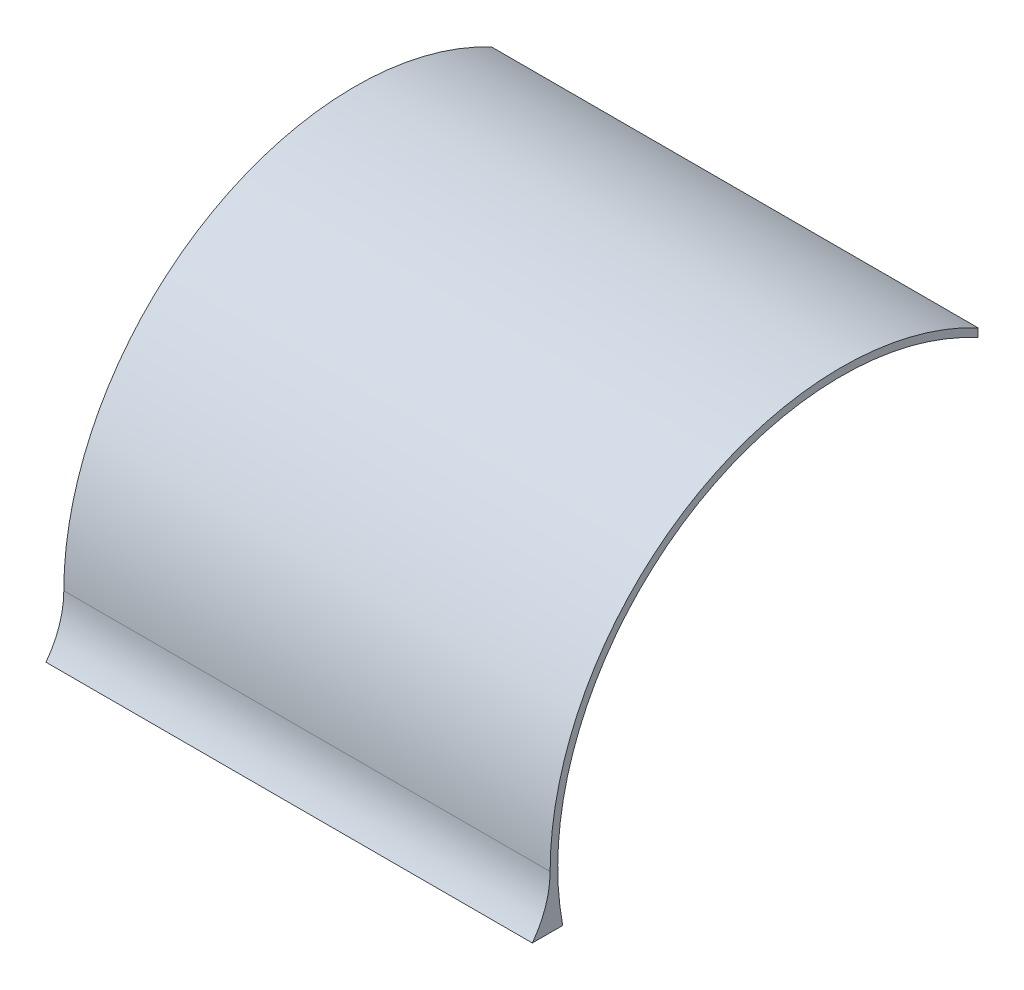
SolidWorks part; units mm, degrees
ref_plane "Alzado" through (0, 0, 0) normal (0, 0, 1) x (1, 0, 0)
ref_plane "Planta" through (0, 0, 0) normal (0, 1, 0) x (1, 0, 0)
ref_plane "Vista lateral" through (0, 0, 0) normal (1, 0, 0) x (0, 0, -1)
sketch "Croquis1" plane through (0, 0, 0) normal (1, 0, 0) x (0, 0, -1)
  line L0 (-94.1687, -17.44) -> (-91.625, -17.44)
  line L1 (45, 84.5393) -> (45, 81.6963)
  circle A0 centre (0, 0) radius 93.27
  circle A1 centre (0, 0) radius 95.77
  dimension "D2" = 93.27
  dimension "D1" = 2.5
  dimension "D3" = 45
  dimension "D4" = 17.44
extrude "Saliente-Extruir1" add sketch "Croquis1" along normal blind 160 contours L1 A1 L0 A0
sketch "Croquis2" plane through (160, 0, 0) normal (1, 0, 0) x (0, 0, -1)
  line L0 (-94.1687, -17.44) -> (-101.625, -17.44)
  line L1 (0, 0) -> (-95.77, 0) construction
  line L2 (-95.77, 0) -> (-95.77, -17.44) construction
  line L3 (-100.177, -17.44) -> (-100.177, -18.7474) construction
  line L4 (-100.177, -18.7474) -> (-97.057, -18.7474) construction
  line L5 (-97.057, -18.7474) -> (-97.057, -17.44) construction
  circle A1 centre (0, 0) radius 95.77 construction
  circle A2 centre (0, 0) radius 93.27 construction
  arc A3 (-95.77, 0) -> (-101.625, -17.44) centre (-124.6714, 0) cw
  arc A4 (-95.77, 0) -> (-94.1687, -17.44) centre (0, 0) ccw
  dimension "D1" = 10
  dimension "D2" = 3.12
extrude "Saliente-Extruir3" add sketch "Croquis2" against normal blind 160
equation "\"D1@Croquis1\"= \"GROSOR_PARED_IMPRESION\""
equation "\"venesta\"= 4'grosor de la venesta"
equation "\"policarbonato\"= 4'grosor del policarbonato"
equation "\"carton_trupan\"= 3'grosor del carton trupan caso laser"
equation "\"ancho_tot\"= 310'ancho tot sin llantas"
equation "\"largo_tot\"= 400'largo tot sin camera"
equation "\"alto_estimado\"= 300'alto estimado sin lidar"
equation "\"altoparaqpaselabotella\"= 75'alto estimado para que encaje la botella"
equation "\"alturaruedaloca\"= 22"
equation "\"anchoruedaloca\"= 35"
equation "\"anchopiso1motorybaterias\"= 150"
equation "\"dist-pisorampa\"= 5"
equation "\"anchoultimopiso\"= 170"
equation "\"paredtrasera\"= 100"
equation "\"agarradorcanasta\"= 275'recolector"
equation "\"alturapiso1y2\"= 80"
equation "\"alturapiso2y3\"= 80"
equation "\"GROSOR_PARED_IMPRESION\"= 2.5"
equation "\"TOLERANCIA\"= 0.06"
equation "\"apertura\"= 70"
equation "\"D2@Croquis1\"=(4-0.02)+ ( \"TOLERANCIA\" * 2 ) + 89.17"
equation "\"D4@Croquis1\"=17.5-\"TOLERANCIA\""
